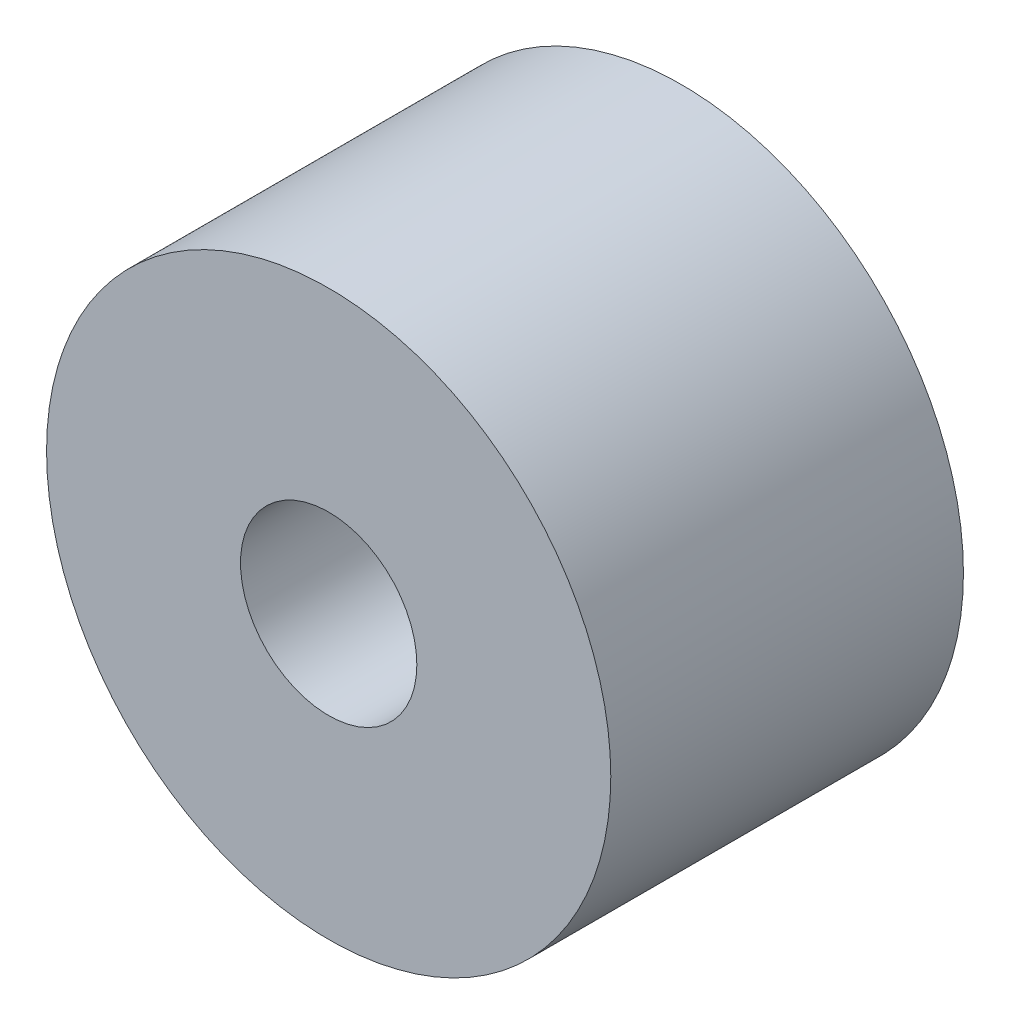
SolidWorks part; units mm, degrees
material "Copper"
ref_plane "Front Plane" through (0, 0, 0) normal (0, 0, 1) x (1, 0, 0)
ref_plane "Top Plane" through (0, 0, 0) normal (0, 1, 0) x (1, 0, 0)
ref_plane "Right Plane" through (0, 0, 0) normal (1, 0, 0) x (0, 0, -1)
sketch "Sketch1" plane through (0, 0, 0) normal (0, 0, 1) x (1, 0, 0)
  circle A0 centre (0, 0) radius 5.08
  circle A1 centre (0, 0) radius 1.5875
  dimension "D1" = 3.175
  dimension "D2" = 10.16
extrude "Boss-Extrude1" add sketch "Sketch1" along normal blind 6.35
